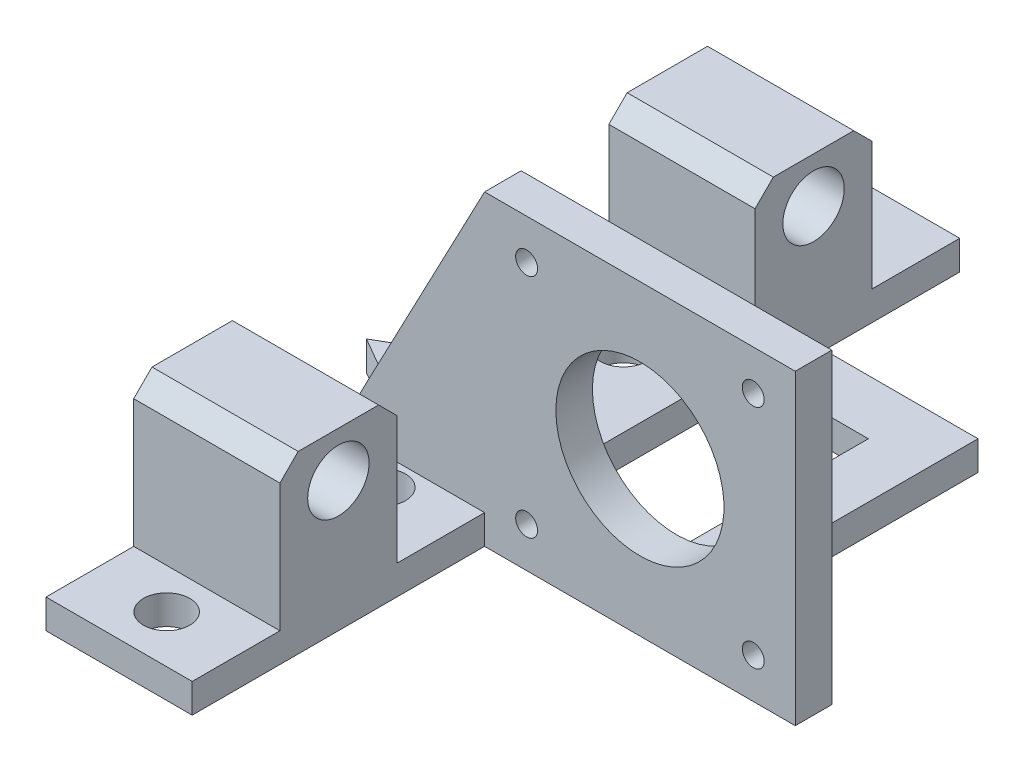
SolidWorks part; units mm, degrees
ref_plane "Front Plane" through (0, 0, 0) normal (0, 0, 1) x (1, 0, 0)
ref_plane "Top Plane" through (0, 0, 0) normal (0, 1, 0) x (1, 0, 0)
ref_plane "Right Plane" through (0, 0, 0) normal (1, 0, 0) x (0, 0, -1)
sketch "Sketch1" plane through (0, 0, 0) normal (0, 1, 0) x (1, 0, 0)
  line L1 (0, 0) -> (20, 0)
  line L2 (0, 0) -> (0, 105)
  line L3 (0, 105) -> (20, 105)
  line L4 (20, 0) -> (20, 105)
  dimension "D1" = 105
  dimension "D2" = 20
extrude "Boss-Extrude1" add sketch "Sketch1" along normal blind 4
sketch "Sketch2" plane through (0, 0, 0) normal (-1, 0, 0) x (0, 0, 1)
  line L0 (-105, 0) -> (0, 0) construction
  line L5 (-12, 21.5) -> (-14.5, 24)
  line L6 (-93, 0) -> (-77, 0)
  line L7 (-93, 0) -> (-93, 24)
  line L8 (-93, 24) -> (-77, 24)
  line L9 (-77, 0) -> (-77, 24)
  line L10 (-105, 0) -> (-93, 0) construction
  line L11 (-79.5, 24) -> (-77, 21.5)
  line L12 (-93, 21.5) -> (-90.5, 24)
  line L13 (-52.5, 0) -> (-52.5, 4) construction
  line L14 (-25.5, 24) -> (-28, 21.5)
  line L15 (-105, 4) -> (0, 4) construction
  line L16 (-28, 0) -> (-28, 24)
  line L17 (-12, 24) -> (-28, 24)
  line L18 (-12, 0) -> (-12, 24)
  line L19 (-12, 0) -> (-28, 0)
  circle A0 centre (-85, 17.8) radius 4.2
  circle A1 centre (-20, 17.8) radius 4.2
  point P10 (-85, 24)
  point P25 (-52.5, 4)
  point P30 (-20, 24)
  line M15 (0, 4) -> (-105, 4)
  dimension "D4" = 8.4
  dimension "D2" = 16
  dimension "D3" = 24
  dimension "D6" = 2.5
  dimension "D7" = 2.5
  dimension "D8" = 2.5
  dimension "D9" = 2.5
  dimension "D1" = 65
  dimension "D5" = 6.2
extrude "Boss-Extrude2" add sketch "Sketch2" against normal up to surface (20 mm away) contours L18 L5 L17 L14 L16 A1 M15 | L12 L7 L9 L11 L8 A0 M15 up to face at (20, 2, -52.5)
sketch "Sketch3" plane through (0, 0, 0) normal (0, -1, 0) x (1, 0, 0)
  line L0 (0, -57.5) -> (-8.6603, -52.5)
  line L1 (0, -105) -> (0, 0) construction
  line L2 (-8.6603, -52.5) -> (0, -47.5)
  line L3 (0, -57.5) -> (0, -47.5)
  point P6 (0, -52.5)
  dimension "D1" = 10
  dimension "D2" = 10
  dimension "D3" = 10
extrude "Boss-Extrude3" add sketch "Sketch3" against normal up to surface (4 mm away) up to face at (10, 4, -99)
sketch "Sketch4" plane through (0, 4, 0) normal (0, 1, 0) x (1, 0, 0)
  line L0 (10, 105) -> (10, 0) construction
  line L1 (20, 105) -> (0, 105) construction
  line L2 (0, 0) -> (20, 0) construction
  circle A0 centre (10, 98.5) radius 3.175
  circle A1 centre (10, 69) radius 3.175
  circle A2 centre (10, 36) radius 3.175
  circle A3 centre (10, 6.5) radius 3.175
  dimension "D1" = 6.35
  dimension "D2" = 6.5
  dimension "D3" = 36
  dimension "D4" = 6.5
  dimension "D5" = 36
extrude "Cut-Extrude1" cut sketch "Sketch4" against normal through all
sketch "Sketch5" plane through (20, 0, 0) normal (1, 0, 0) x (0, 0, -1)
  line L0 (0, 0) -> (105, 0) construction
  line L1 (45, 0) -> (40, 0)
  line L2 (45, 0) -> (45, 42)
  line L3 (45, 42) -> (40, 42)
  line L4 (40, 0) -> (40, 42)
  dimension "D1" = 42
  dimension "D2" = 5
  dimension "D3" = 7.5
extrude "Boss-Extrude4" add sketch "Sketch5" along normal blind 42.5
sketch "Sketch6" plane through (0, 0, -45) normal (0, 0, -1) x (-1, 0, 0)
  line L0 (-41.25, 42) -> (-41.25, 0) construction
  line L1 (-62.5, 42) -> (-20, 42) construction
  line L2 (-62.5, 0) -> (-20, 0) construction
  line L3 (-62.5, 21) -> (-20, 21) construction
  line L4 (-62.5, 0) -> (-62.5, 42) construction
  line L5 (-20, 4) -> (-20, 42) construction
  circle A0 centre (-41.25, 21) radius 11.5
  circle A1 centre (-56.75, 36.5) radius 1.5
  circle A5 centre (-25.75, 36.5) radius 1.5
  circle A6 centre (-25.75, 5.5) radius 1.5
  circle A7 centre (-56.75, 5.5) radius 1.5
  point P16 (-41, 21)
  point P17 (-41, 21)
  point P18 (-54.4553, 35.1694)
  point P21 (-55.8866, 21)
  dimension "D3" = 3
  dimension "D4" = 23
  dimension "D1" = 15.5
  dimension "D2" = 15.5
extrude "Cut-Extrude2" cut sketch "Sketch6" against normal through all
sketch "Sketch7" plane through (0, 0, -40) normal (0, 0, 1) x (1, 0, 0)
  line L0 (20, 42) -> (0, 4)
  line L1 (0, 4) -> (20, 4)
  line L2 (20, 4) -> (20, 42)
  point P3 (-15.6451, 19.3766)
extrude "Boss-Extrude5" add sketch "Sketch7" against normal up to surface (5 mm away) up to face at (58.25, 5.5, -45)
sketch "Sketch8" plane through (0, 0, 0) normal (0, -1, 0) x (1, 0, 0)
  line L0 (45, -45) -> (45, -82.5)
  line L1 (62.5, -45) -> (20, -45) construction
  line L2 (45, -82.5) -> (20, -82.5)
  line L3 (20, -45) -> (20, -105) construction
  line L4 (20, -82.5) -> (20, -75)
  line L5 (20, -75) -> (37.5, -75)
  line L6 (37.5, -75) -> (37.5, -45)
  line L7 (37.5, -45) -> (45, -45)
  point P4 (59.0309, -45)
  point P11 (41.25, -45)
  point P12 (41.25, -45)
  point P13 (20, -91.4792)
  dimension "D1" = 7.5
extrude "Boss-Extrude6" add sketch "Sketch8" against normal up to surface (4 mm away) up to face at (10, 4, -3.325)
equation "\"8mm hole\" = 8.4mm"
equation "\"D4@Sketch2\"= \"8mm hole\""
equation "\"22mm hole\"= 23mm"
equation "\"15mm hole\"= 15.8mm"
equation "\"bed height offset\"= 3mm"
equation "\"D3@Sketch2\"= 21 + \"bed height offset\""
equation "\"D4@Sketch6\"= \"22mm hole\""
